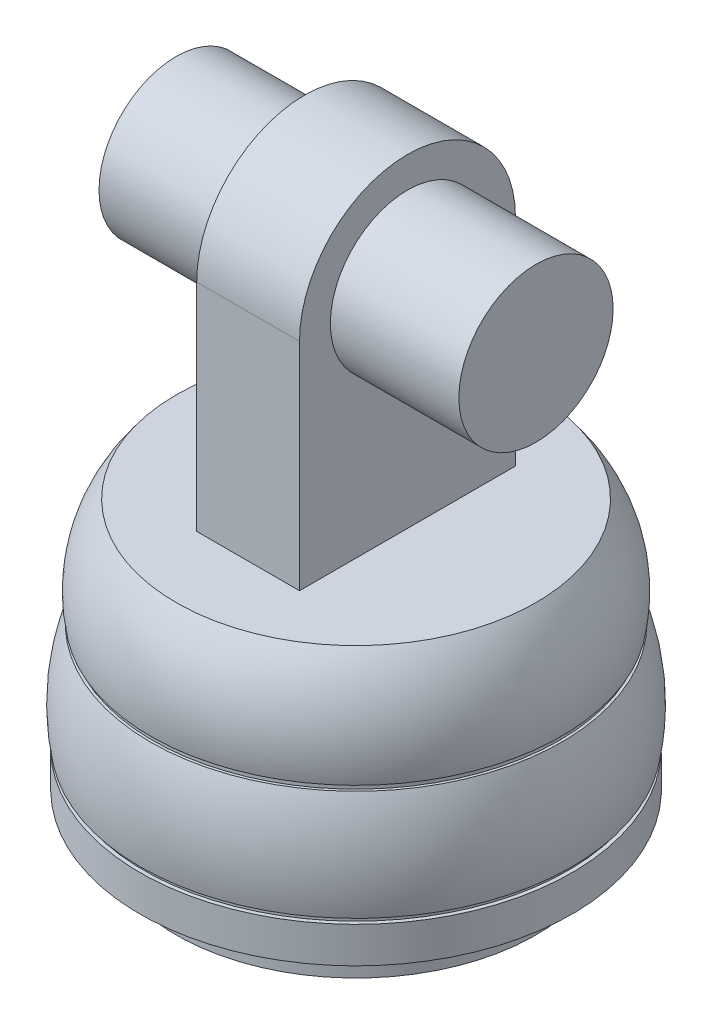
SolidWorks part; units mm, degrees
ref_plane "Front Plane" through (0, 0, 0) normal (0, 0, 1) x (1, 0, 0)
ref_plane "Top Plane" through (0, 0, 0) normal (0, 1, 0) x (1, 0, 0)
ref_plane "Right Plane" through (0, 0, 0) normal (1, 0, 0) x (0, 0, -1)
sketch "Sketch1" plane through (0, 0, 0) normal (0, 0, 1) x (1, 0, 0)
  line L0 (-35, 0) -> (0, 0)
  line L1 (0, 0) -> (0, -20)
  line L2 (0, -20) -> (-40, -20)
  arc A0 (-40, -20) -> (-35, 0) centre (-15.404, -15.524) cw
  dimension "D4" = 25
  dimension "D1" = 35
  dimension "D2" = 20
  dimension "D3" = 40
revolve "Revolve1" add sketch "Sketch1" angle 360 about L1
sketch "Sketch2" plane through (0, -20, 0) normal (0, -1, 0) x (1, 0, 0)
  circle A0 centre (0, 0) radius 39.5
  dimension "D1" = 79
extrude "Boss-Extrude1" add sketch "Sketch2" along normal blind 1
sketch "Sketch3" plane through (0, 0, 0) normal (1, 0, 0) x (0, 0, -1)
  line L0 (0, -21) -> (-40, -21)
  line L1 (-39.5, -21) -> (39.5, -21) construction
  line L2 (0, -21) -> (0, -41)
  line L3 (0, -41) -> (-42, -41)
  arc A0 (-42, -41) -> (-40, -21) centre (-5.5677, -34.5432) cw
  dimension "D4" = 37
  dimension "D1" = 40
  dimension "D2" = 20
  dimension "D3" = 42
revolve "Revolve2" add sketch "Sketch3" angle 360 about L2
sketch "Sketch4" plane through (0, -41, 0) normal (0, -1, 0) x (1, 0, 0)
  circle A0 centre (0, 0) radius 41.25
  dimension "D1" = 82.5
extrude "Boss-Extrude2" add sketch "Sketch4" along normal blind 1
sketch "Sketch5" plane through (0, -42, 0) normal (0, -1, 0) x (1, 0, 0)
  circle A0 centre (0, 0) radius 42
  dimension "D1" = 84
extrude "Boss-Extrude3" add sketch "Sketch5" along normal blind 7
sketch "Sketch6" plane through (0, -49, 0) normal (0, -1, 0) x (1, 0, 0)
  circle A0 centre (0, 0) radius 35
  dimension "D1" = 70
extrude "Boss-Extrude4" add sketch "Sketch6" along normal blind 7
sketch "Sketch7" plane through (0, -49, 0) normal (0, -1, 0) x (1, 0, 0)
  line L1 (38.4461, -2.2339) -> (40.3807, -1.117)
  line L2 (40.3807, -1.117) -> (40.3807, 1.117)
  line L3 (40.3807, 1.117) -> (38.4461, 2.2339)
  line L4 (38.4461, 2.2339) -> (36.5114, 1.117)
  line L5 (36.5114, 1.117) -> (36.5114, -1.117)
  line L6 (36.5114, -1.117) -> (38.4461, -2.2339)
  line L7 (38.4461, -1.5469) -> (39.7857, -0.7735)
  line L8 (39.7857, -0.7735) -> (39.7857, 0.7735)
  line L9 (39.7857, 0.7735) -> (38.4461, 1.5469)
  line L10 (38.4461, 1.5469) -> (37.1064, 0.7735)
  line L11 (37.1064, 0.7735) -> (37.1064, -0.7735)
  line L12 (37.1064, -0.7735) -> (38.4461, -1.5469)
  circle A0 centre (38.4461, 0) radius 1.9347 construction
  circle A1 centre (38.4461, 0) radius 1.3397 construction
extrude "Boss-Extrude5" add sketch "Sketch7" along normal blind 1
pattern_circular "CirPattern1" count 10 over 360 about axis through (0, 0, 0) along (0, 1, 0) of "Boss-Extrude5"
sketch "Sketch9" plane through (0, -56, 0) normal (0, -1, 0) x (1, 0, 0)
  circle A0 centre (0, 0) radius 15
  dimension "D1" = 30
extrude "Boss-Extrude6" add sketch "Sketch9" along normal blind 10
sketch "Sketch10" plane through (0, 0, 0) normal (0, 1, 0) x (1, 0, 0)
  line L0 (0, 21) -> (0, -21) construction
  line L1 (-10, 21) -> (-10, -21)
  line L2 (10, 21) -> (10, -21)
  line L3 (-10, 21) -> (10, 21)
  line L4 (-10, -21) -> (10, -21)
  point P4 (0, 0)
  dimension "D1" = 42
  dimension "D2" = 10
  dimension "D3" = 10
extrude "Boss-Extrude7" add sketch "Sketch10" along normal blind 42
sketch "Sketch11" plane through (10, 0, 0) normal (1, 0, 0) x (0, 0, -1)
  line L0 (-21, 42) -> (21, 42) construction
  line L1 (-21, 42) -> (21, 42)
  arc A0 (21, 42) -> (-21, 42) centre (0, 42) ccw
extrude "Boss-Extrude8" add sketch "Sketch11" against normal up to vertex
sketch "Sketch12" plane through (-10, 0, 0) normal (-1, 0, 0) x (0, 0, 1)
  circle A0 centre (0, 42) radius 15
  dimension "D1" = 30
extrude "Boss-Extrude9" add sketch "Sketch12" along normal blind 25
sketch "Sketch13" plane through (10, 0, 0) normal (1, 0, 0) x (0, 0, -1)
  circle A0 centre (0, 42) radius 15
  dimension "D1" = 30
extrude "Boss-Extrude10" add sketch "Sketch13" along normal blind 25
